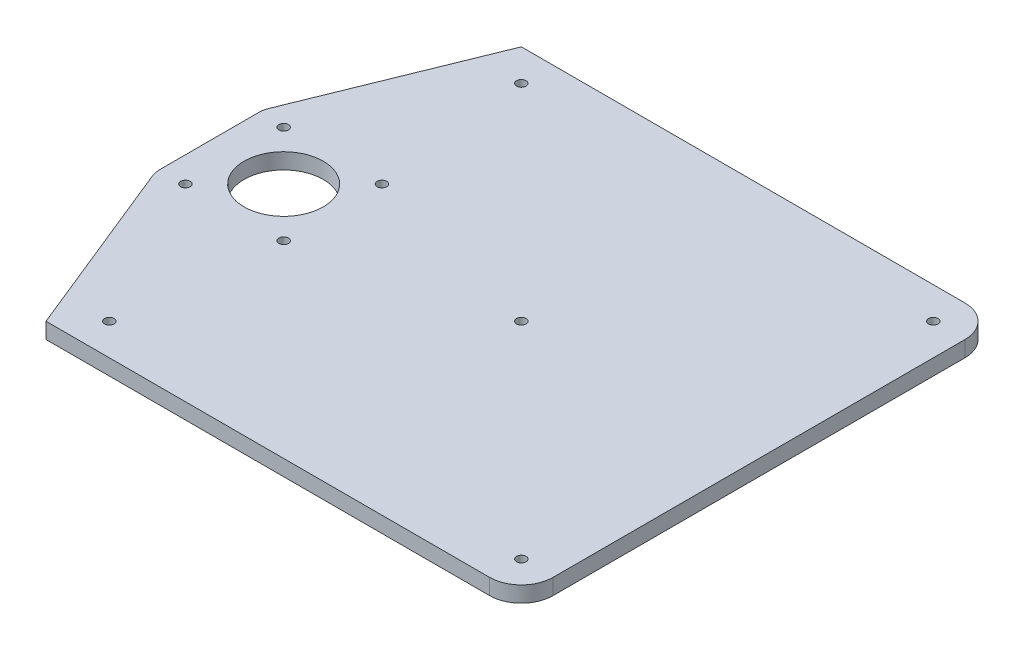
SolidWorks part; units mm, degrees
ref_plane "Front Plane" through (0, 0, 0) normal (0, 0, 1) x (1, 0, 0)
ref_plane "Top Plane" through (0, 0, 0) normal (0, 1, 0) x (1, 0, 0)
ref_plane "Right Plane" through (0, 0, 0) normal (1, 0, 0) x (0, 0, -1)
sketch "Sketch1" plane through (0, 0, 0) normal (0, 1, 0) x (1, 0, 0)
  line L1 (-75, -75) -> (65, -75)
  line L3 (-75, 75) -> (65, 75)
  line L4 (75, -65) -> (75, 65)
  line L5 (-75, -75) -> (75, 75) construction
  line L6 (-75, 75) -> (75, -75) construction
  line L11 (-90.5, -15.5) -> (-59.5, 15.5) construction
  line L12 (-90.5, 15.5) -> (-59.5, -15.5) construction
  line L16 (-97.9134, -18.5069) -> (-75, -75)
  line L17 (-98.5, -15.5) -> (-98.5, 15.5)
  line L18 (-98.5, 0) -> (-75, 0) construction
  line L19 (-97.9134, 18.5069) -> (-75, 75)
  circle A0 centre (-90.5, 15.5) radius 1.5
  circle A1 centre (-90.5, -15.5) radius 1.5
  circle A2 centre (-59.5, -15.5) radius 1.5
  circle A3 centre (-59.5, 15.5) radius 1.5
  circle A4 centre (-75, 0) radius 12.5
  arc A5 (-98.5, -15.5) -> (-97.9134, -18.5069) centre (-90.5, -15.5) ccw
  arc A6 (-98.5, 15.5) -> (-97.9134, 18.5069) centre (-90.5, 15.5) cw
  arc A7 (65, -75) -> (75, -65) centre (65, -65) ccw
  arc A8 (65, 75) -> (75, 65) centre (65, 65) cw
  circle A9 centre (-65, 65) radius 1.5
  circle A10 centre (65, 65) radius 1.5
  circle A11 centre (65, -65) radius 1.5
  circle A12 centre (-65, -65) radius 1.5
  circle A13 centre (0, 0) radius 1.5
  point P0 (0, 0)
  point P6 (-75, 0)
  dimension "D3" = 3
  dimension "D2" = 25
  dimension "D6" = 10
  dimension "D7" = 3
  dimension "D8" = 3
  dimension "D1" = 150
  dimension "D4" = 31
  dimension "D5" = 8
extrude "Boss-Extrude1" add sketch "Sketch1" along normal blind 5
